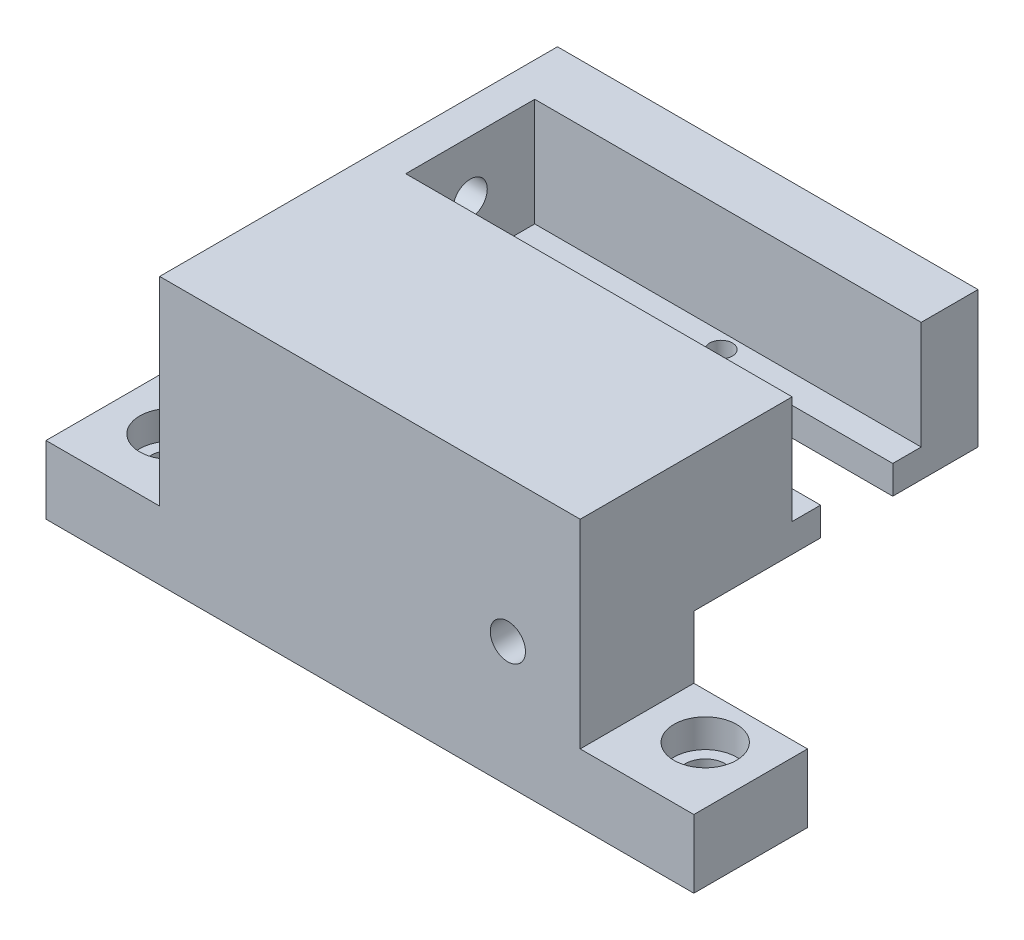
SolidWorks part; units mm, degrees
ref_plane "Front Plane" through (0, 0, 0) normal (0, 0, 1) x (1, 0, 0)
ref_plane "Top Plane" through (0, 0, 0) normal (0, 1, 0) x (1, 0, 0)
ref_plane "Right Plane" through (0, 0, 0) normal (1, 0, 0) x (0, 0, -1)
sketch "Sketch1" plane through (0, 0, 0) normal (0, 1, 0) x (1, 0, 0)
  line L1 (-37, 35) -> (37, 35)
  line L2 (-37, 35) -> (-37, -35)
  line L3 (-37, -35) -> (37, -35)
  line L4 (37, 35) -> (37, -35)
  line L5 (-37, 35) -> (37, -35) construction
  line L6 (-37, -35) -> (37, 35) construction
  point P0 (0, 0)
  dimension "D1" = 74
  dimension "D2" = 70
extrude "Boss-Extrude1" add sketch "Sketch1" along normal blind 47
sketch "Sketch2" plane through (37, 0, 0) normal (1, 0, 0) x (0, 0, -1)
  line L0 (-35, 47) -> (35, 47) construction
  line L1 (2.3, 47) -> (25, 47)
  line L2 (2.3, 47) -> (2.3, 28)
  line L3 (2.3, 28) -> (25, 28)
  line L4 (25, 47) -> (25, 28)
  line L6 (35, 47) -> (35, 0) construction
  dimension "D1" = 19
  dimension "D2" = 22.7
  dimension "D3" = 10
extrude "Cut-Extrude1" cut sketch "Sketch2" against normal blind 68
sketch "Sketch7" plane through (0, 0, -35) normal (0, 0, -1) x (-1, 0, 0)
  line L1 (-37, 0) -> (13, 0)
  line L2 (-37, 0) -> (-37, 23)
  line L3 (-37, 23) -> (13, 23)
  line L4 (13, 0) -> (13, 23)
  dimension "D1" = 23
  dimension "D2" = 50
extrude "Cut-Extrude4" cut sketch "Sketch7" against normal blind 50
sketch "Sketch8" plane through (0, 0, 35) normal (0, 0, 1) x (1, 0, 0)
  line L0 (-37, 0) -> (37, 0) construction
  line L1 (37, 47) -> (37, 0) construction
  circle A0 centre (24.27, 22) radius 3.1
  dimension "D1" = 6.2
  dimension "D2" = 22
  dimension "D3" = 12.73
extrude "Cut-Extrude5" cut sketch "Sketch8" against normal blind 25
sketch "Sketch9" plane through (37, 0, 0) normal (1, 0, 0) x (0, 0, -1)
  line L0 (-15, 23) -> (-15, 0) construction
  line L1 (-35, 0) -> (-15, 0)
  line L2 (-35, 0) -> (-35, 12)
  line L3 (-35, 12) -> (-15, 12)
  line L4 (-15, 0) -> (-15, 12)
  dimension "D1" = 12
extrude "Boss-Extrude3" add sketch "Sketch9" along normal blind 20
sketch "Sketch10" plane through (-37, 0, 0) normal (-1, 0, 0) x (0, 0, 1)
  line L0 (-35, 47) -> (-35, 0) construction
  line L1 (-35, 0) -> (35, 0)
  line L2 (-35, 0) -> (-35, 12)
  line L3 (-35, 12) -> (35, 12)
  line L4 (35, 0) -> (35, 12)
  line L5 (35, 47) -> (35, 0) construction
  dimension "D1" = 12
extrude "Boss-Extrude4" add sketch "Sketch10" along normal blind 20
sketch "Sketch12" plane through (0, 12, 0) normal (0, 1, 0) x (1, 0, 0)
  line L0 (-57, -35) -> (-57, 35) construction
  line L4 (-57, 35) -> (-37, 35) construction
  circle A0 centre (-47, 23) radius 3.5
  dimension "D1" = 7
  dimension "D2" = 10
  dimension "D3" = 12
extrude "Cut-Extrude6" cut sketch "Sketch12" against normal blind 20
mirror "Mirror1" about plane through (0, 0, 0) normal (0, 0, 1) of "Cut-Extrude6" second plane through (0, 0, 0) second plane normal (1, 0, 0)
sketch "Sketch13" plane through (0, 12, 0) normal (0, 1, 0) x (1, 0, 0)
  circle A0 centre (-47, -23) radius 5.5
  dimension "D1" = 11
extrude "Cut-Extrude7" cut sketch "Sketch13" against normal blind 5
mirror "Mirror2" about plane through (0, 0, 0) normal (0, 0, 1) of "Cut-Extrude7" second plane through (0, 0, 0) second plane normal (1, 0, 0)
sketch "Sketch14" plane through (-31, 0, 0) normal (1, 0, 0) x (0, 0, -1)
  line L0 (2.3, 28) -> (25, 28) construction
  circle A0 centre (13.65, 37.5) radius 3
  point P4 (13.65, 28)
  dimension "D1" = 9.5
  dimension "D2" = 6
extrude "Cut-Extrude8" cut sketch "Sketch14" against normal blind 10
sketch "Sketch15" plane through (37, 0, 0) normal (1, 0, 0) x (0, 0, -1)
  line L0 (2.3, 28) -> (25, 28) construction
  line L1 (7.3, 28) -> (20, 28)
  line L2 (7.3, 28) -> (7.3, 23)
  line L3 (7.3, 23) -> (20, 23)
  line L4 (20, 28) -> (20, 23)
  line L5 (-15, 23) -> (35, 23) construction
  line L6 (2.3, 47) -> (2.3, 28) construction
  line L7 (25, 28) -> (25, 47) construction
  point P10 (20, 25.5)
  dimension "D1" = 5
  dimension "D2" = 5
extrude "Cut-Extrude9" cut sketch "Sketch15" against normal blind 20
sketch "Sketch16" plane through (0, 28, 0) normal (0, 1, 0) x (1, 0, 0)
  line L0 (-31, 2.3) -> (-31, 25) construction
  line L1 (-31, 25) -> (37, 25) construction
  line L2 (-31, 2.3) -> (37, 2.3) construction
  circle A0 centre (4.53, 5.05) radius 2
  circle A1 centre (4.53, 22.25) radius 2
  dimension "D1" = 4
  dimension "D2" = 4
  dimension "D3" = 35.53
  dimension "D4" = 2.75
  dimension "D5" = 35.53
  dimension "D6" = 2.75
extrude "Cut-Extrude10" cut sketch "Sketch16" against normal through all
